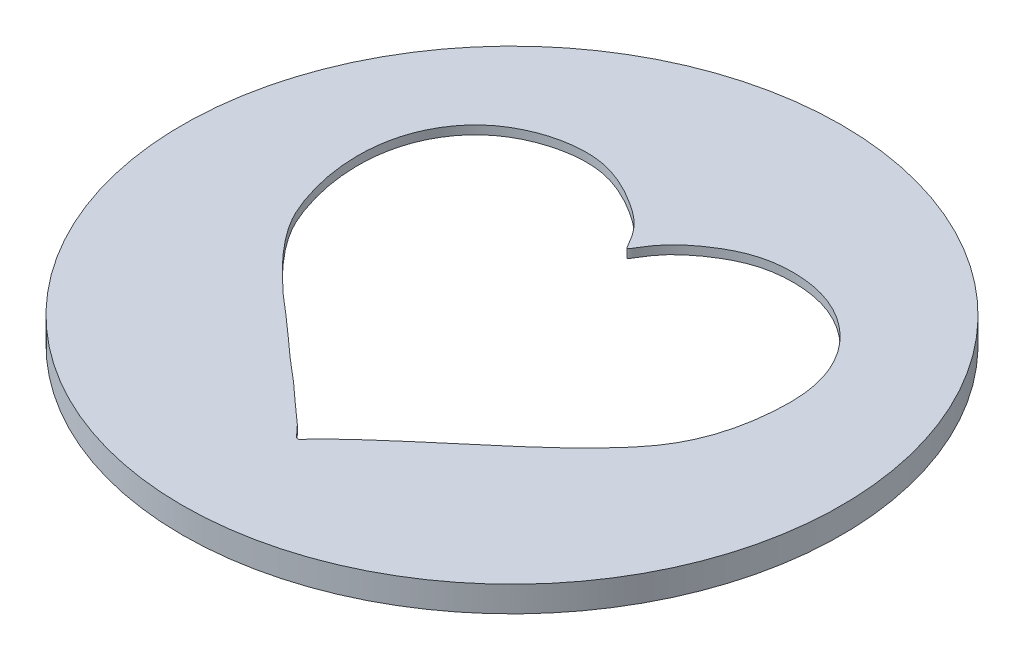
SolidWorks part; units mm, degrees
ref_plane "前视基准面" through (0, 0, 0) normal (0, 0, 1) x (1, 0, 0)
ref_plane "上视基准面" through (0, 0, 0) normal (0, 1, 0) x (1, 0, 0)
ref_plane "右视基准面" through (0, 0, 0) normal (1, 0, 0) x (0, 0, -1)
other "Configuration Table"
sketch "草图1" plane through (0, 0, 0) normal (0, 1, 0) x (1, 0, 0)
  line L0 (72.5003, 135.938) -> (362.5014, 135.938) construction
  line L1 (210, 543.5) -> (1010, 543.5) construction
  circle A0 centre (35, 20) radius 38.5
  spline S0 degree 3 poles (10.5357, 21.1851) (9.521, 26.388) (10.3286, 32.5995) (13.7303, 38.1575) (19.5425, 40.8305) (25.7064, 40.9707) (31.0102, 38.1127) (33.6001, 35.9703) (34.9905, 33.3202) (36.3119, 35.6925) (38.0018, 37.388) (41.2161, 39.4694) (44.0936, 40.5737) (47.4929, 40.9039) (52.375, 40.1747) (57.2902, 36.8273) (60.0138, 31.2516) (60.2338, 24.3525) (58.5841, 17.3184) (53.4399, 11.3634) (46.8074, 5.3415) (40.5704, 0.3264) (36.7369, -3.3248) (35.7098, -4.2565) (35.029, -5.3175) (33.6785, -3.6202) (31.9126, -2.2321) (28.9375, 0.6165) (25.7614, 3.1465) (22.7988, 6.0122) (20.0462, 8.2223) (17.8173, 10.3337) (15.8704, 12.2955) (14.0189, 14.4538) (12.2609, 16.9636) (10.5357, 21.1851) (9.521, 26.388) (10.3286, 32.5995) knots -0.087533 -0.065854 -0.045447 0 0.034602 0.073231 0.120202 0.150836 0.190181 0.227348 0.230138 0.232668 0.266921 0.287053 0.303469 0.326329 0.351886 0.397575 0.434239 0.467156 0.529382 0.567588 0.616606 0.703531 0.716154 0.724764 0.729948 0.734662 0.757644 0.780075 0.811318 0.836747 0.859224 0.879345 0.895881 0.912467 0.934146 0.954553 1 1.034602 1.073231 1.120202 only from (9.8477, 26.9637) to (9.8477, 26.9637)
  point P9 (37.1749, -3.7601)
  point P11 (36.5689, -3.4715)
  dimension "D1" = 77
  dimension "D3" = 20
extrude "凸台-拉伸1" add sketch "草图1" along normal blind 1
sketch "草图2" plane through (0, 0, 0) normal (0, -1, 0) x (-1, 0, 0)
  circle A0 centre (-35, 20) radius 38.5
  circle A1 centre (-35, 20) radius 37.5
  circle A2 centre (-35, 20) radius 38.5 construction
  dimension "D2" = 0
  dimension "D1" = 1
extrude "凸台-拉伸2" add sketch "草图2" along normal blind 2
sketch "草图3" plane through (0, 1, 0) normal (0, 1, 0) x (1, 0, 0)
  circle A0 centre (35, 20) radius 37.5
  circle A1 centre (35, 20) radius 38.5
  circle A2 centre (35, 20) radius 38.5 construction
  dimension "D2" = 0
  dimension "D1" = 1
extrude "凸台-拉伸3" add sketch "草图3" against normal blind 1
